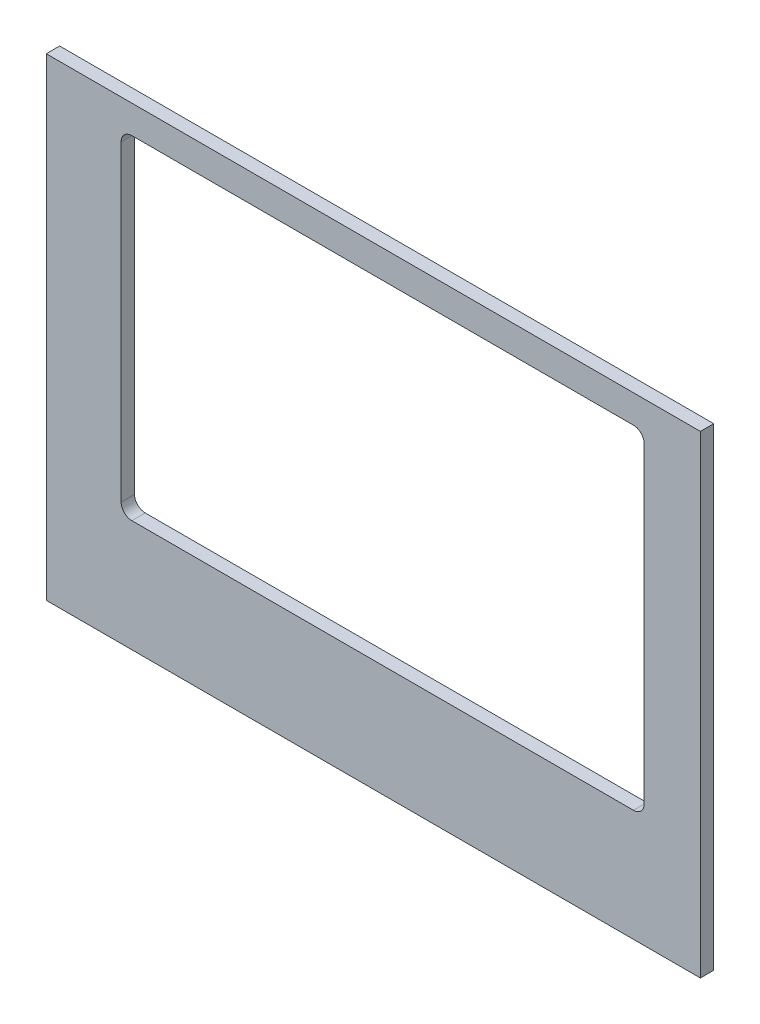
SolidWorks part; units mm, degrees
ref_plane "Front Plane" through (0, 0, 0) normal (0, 0, 1) x (1, 0, 0)
ref_plane "Top Plane" through (0, 0, 0) normal (0, 1, 0) x (1, 0, 0)
ref_plane "Right Plane" through (0, 0, 0) normal (1, 0, 0) x (0, 0, -1)
sketch "Sketch1" plane through (0, 0, 0) normal (0, 0, 1) x (1, 0, 0)
  line L2 (-73.0725, -29.6525) -> (-10.985, -29.6525)
  line L4 (-10.985, 49.5225) -> (51.1025, 49.5225)
  line L5 (51.1025, 49.5225) -> (51.1025, 9.935)
  line L6 (51.1025, 9.935) -> (51.1025, -29.6525)
  line L7 (51.1025, -29.6525) -> (-10.985, -29.6525)
  line L8 (-73.0725, -29.6525) -> (-73.0725, 9.935)
  line L14 (-73.0725, 47.935) -> (-73.0725, 49.5225)
  line L15 (-73.0725, 49.5225) -> (-10.985, 49.5225)
  line L16 (-73.0725, 47.935) -> (-73.0725, 9.935)
  line L26 (61.2775, 1.5875) -> (61.2775, -56.1975)
  line L27 (61.2775, -56.1975) -> (0, -56.1975)
  line L28 (0, -56.1975) -> (-90.8525, -56.1975)
  line L30 (-90.8525, 5.3021) -> (-90.8525, -56.1975)
  line L31 (-90.8525, 5.3021) -> (-90.8525, 56.1975)
  line L33 (-7.1043, 56.1975) -> (-90.8525, 56.1975)
  line L34 (-7.1043, 56.1975) -> (61.2775, 56.1975)
  line L35 (61.2775, 56.1975) -> (61.2775, 1.5875)
  point P0 (0, 0)
extrude "Boss-Extrude1" add sketch "Sketch1" along normal blind 3.175
sketch "Sketch2" plane through (61.2775, 0, 0) normal (1, 0, 0) x (0, 0, -1)
  line L1 (-3.175, 56.1975) -> (0, 56.1975)
  line L2 (-3.175, 56.1975) -> (-3.175, -56.1975)
  line L3 (-3.175, -56.1975) -> (0, -56.1975)
  line L4 (0, 56.1975) -> (0, -56.1975)
extrude "Boss-Extrude2" add sketch "Sketch2" along normal blind 3.175
fillet "Fillet1" radius 2.54 4 edges at (-73.0725, -29.6525, 1.5875) (51.1025, -29.6525, 1.5875) (51.1025, 49.5225, 1.5875) (-73.0725, 49.5225, 1.5875)
